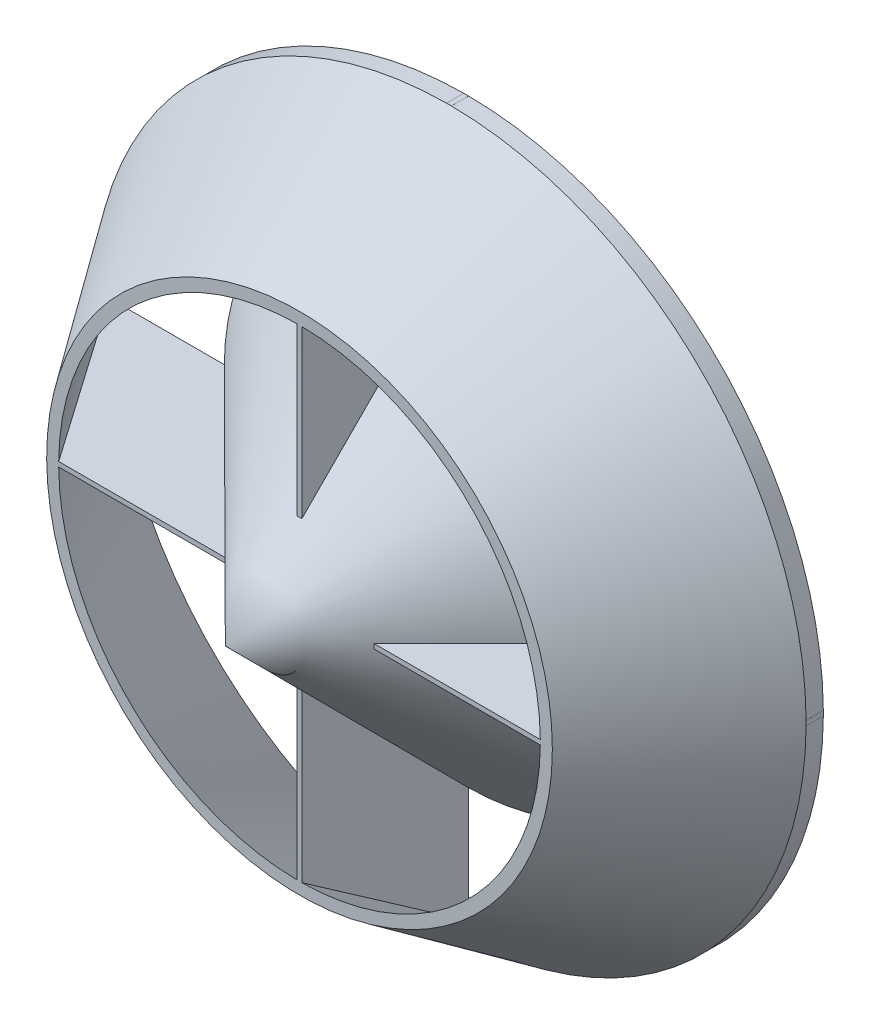
SolidWorks part; units mm, degrees
ref_plane "Front Plane" through (0, 0, 0) normal (0, 0, 1) x (1, 0, 0)
ref_plane "Top Plane" through (0, 0, 0) normal (0, 1, 0) x (1, 0, 0)
ref_plane "Right Plane" through (0, 0, 0) normal (1, 0, 0) x (0, 0, -1)
sketch "Sketch1" plane through (0, 0, 0) normal (1, 0, 0) x (0, 0, -1)
  line L0 (0, 101.6) -> (-101.15, 0)
  line L1 (0, 165) -> (0, -165) construction
  line L2 (-101.15, 0) -> (-96.9167, 0)
  line L3 (55.6325, 0) -> (-55.6325, 0) construction
  line L4 (-96.9167, 0) -> (0, 97.3479)
  line L5 (0, 97.3479) -> (0, 101.6)
  dimension "D1" = 101.6
  dimension "D2" = 101.15
  dimension "D3" = 3
revolve "Revolve1" add sketch "Sketch1" angle 360 about L2
sketch "Sketch3" plane through (0, 0, 0) normal (0, 0, 1) x (1, 0, 0)
  line L0 (-1, 1) -> (-150, 1)
  line L1 (150, 1) -> (-150, 1) construction
  line L2 (150, 1) -> (150, -1) construction
  line L3 (150, -1) -> (-150, -1) construction
  line L4 (-150, 1) -> (-150, -1) construction
  line L5 (150, 1) -> (-150, -1) construction
  line L6 (150, -1) -> (-150, 1) construction
  line L7 (-1, -150) -> (1, -150) construction
  line L8 (-1, -150) -> (-1, 150) construction
  line L9 (-1, 150) -> (1, 150) construction
  line L10 (1, -150) -> (1, 150) construction
  line L11 (-1, -150) -> (1, 150) construction
  line L12 (-1, 150) -> (1, -150) construction
  line L13 (-150, 1) -> (-150, -1)
  line L14 (-150, -1) -> (-1, -1)
  line L15 (-1, -1) -> (-1, -150)
  line L16 (-1, -150) -> (1, -150)
  line L17 (1, -150) -> (1, -1)
  line L18 (1, -1) -> (150, -1)
  line L19 (150, -1) -> (150, 1)
  line L20 (150, 1) -> (1, 1)
  line L21 (1, 1) -> (1, 150)
  line L22 (1, 150) -> (-1, 150)
  line L23 (-1, 150) -> (-1, 1)
  point P0 (0, 0)
  point P6 (0, 0)
  dimension "D1" = 2
  dimension "D2" = 2
  dimension "D3" = 300
  dimension "D4" = 300
extrude "Boss-Extrude1" add sketch "Sketch3" along normal blind 70
sketch "Sketch5" plane through (0, 0, 0) normal (1, 0, 0) x (0, 0, -1)
  line L0 (-96.9167, 0) -> (6.1339, 103.0413)
  line L1 (6.1339, 103.0413) -> (0, 0)
  line L2 (0, 0) -> (-96.9167, 0)
  point P3 (0, 0)
revolve "Cut-Revolve1" cut sketch "Sketch5" angle 360 about L2
sketch "Sketch6" plane through (0, 0, 0) normal (1, 0, 0) x (0, 0, -1)
  line L0 (0, 150) -> (-70, 101.1451)
  line L1 (-70, 31.2726) -> (-70, 150) construction
  line L2 (-70, 101.1451) -> (-70, 106.1952)
  line L3 (-70, 106.1952) -> (-7.2359, 150)
  line L4 (-70, 150) -> (0, 150) construction
  line L5 (-7.2359, 150) -> (0, 150)
  line L6 (-106.2049, 0) -> (15.4868, 0) construction
  line L7 (55.6325, 0) -> (-55.6325, 0) construction
revolve "Revolve2" add sketch "Sketch6" angle 360 about L6
sketch "Sketch7" plane through (0, 0, 0) normal (1, 0, 0) x (0, 0, -1)
  line L0 (-7.2359, 149.9967) -> (-70, 106.1905)
  line L1 (-70, 106.1905) -> (-70, 150)
  line L2 (-7.2359, 149.9967) -> (-4.6472, 151.8034)
  line L3 (-108.5473, 0) -> (14.0021, 0) construction
  line L4 (55.6325, 0) -> (-55.6325, 0) construction
  line L5 (-4.6472, 151.8034) -> (-70, 151.8034)
  line L6 (-70, 151.8034) -> (-70, 150)
revolve "Cut-Revolve2" cut sketch "Sketch7" angle 360 about L3
